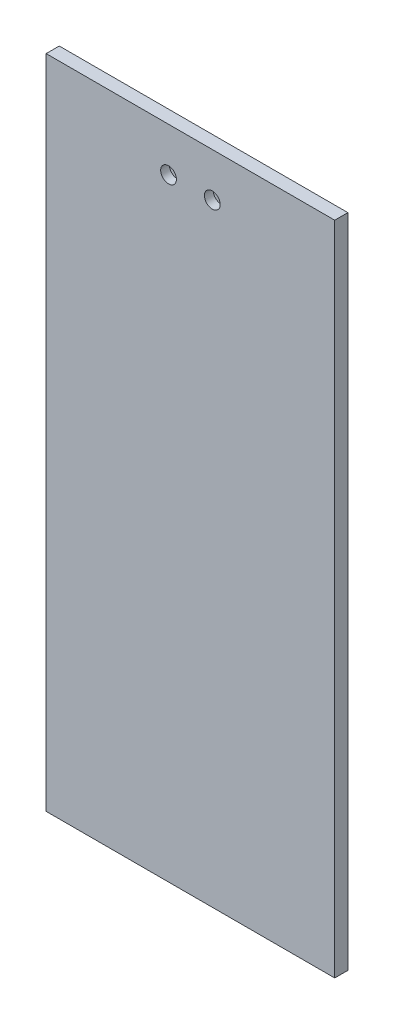
SolidWorks part; units mm, degrees
ref_plane "Front Plane" through (0, 0, 0) normal (0, 0, 1) x (1, 0, 0)
ref_plane "Top Plane" through (0, 0, 0) normal (0, 1, 0) x (1, 0, 0)
ref_plane "Right Plane" through (0, 0, 0) normal (1, 0, 0) x (0, 0, -1)
sketch "Sketch1" plane through (0, 0, 0) normal (0, 1, 0) x (1, 0, 0)
  line L0 (0, 0) -> (65.96, 0)
  line L1 (65.96, 0) -> (65.96, 3)
  line L2 (65.96, 3) -> (0, 3)
  line L3 (0, 3) -> (0, 0)
  dimension "D1" = 3
  dimension "D2" = 65.96
extrude "Boss-Extrude1" add sketch "Sketch1" along normal blind 150
sketch "Sketch3" plane through (0, 0, 0) normal (0, 0, 1) x (1, 0, 0)
  line L0 (0, 150) -> (65.96, 150) construction
  line L1 (32.98, 150) -> (32.98, 127.9408) construction
  circle A0 centre (27.98, 140) radius 1.8
  circle A1 centre (37.98, 140) radius 1.8
  point P8 (0, 0)
  dimension "D1" = 3.6
  dimension "D3" = 10
  dimension "D2" = 10
extrude "Cut-Extrude1" cut sketch "Sketch3" against normal blind 2
